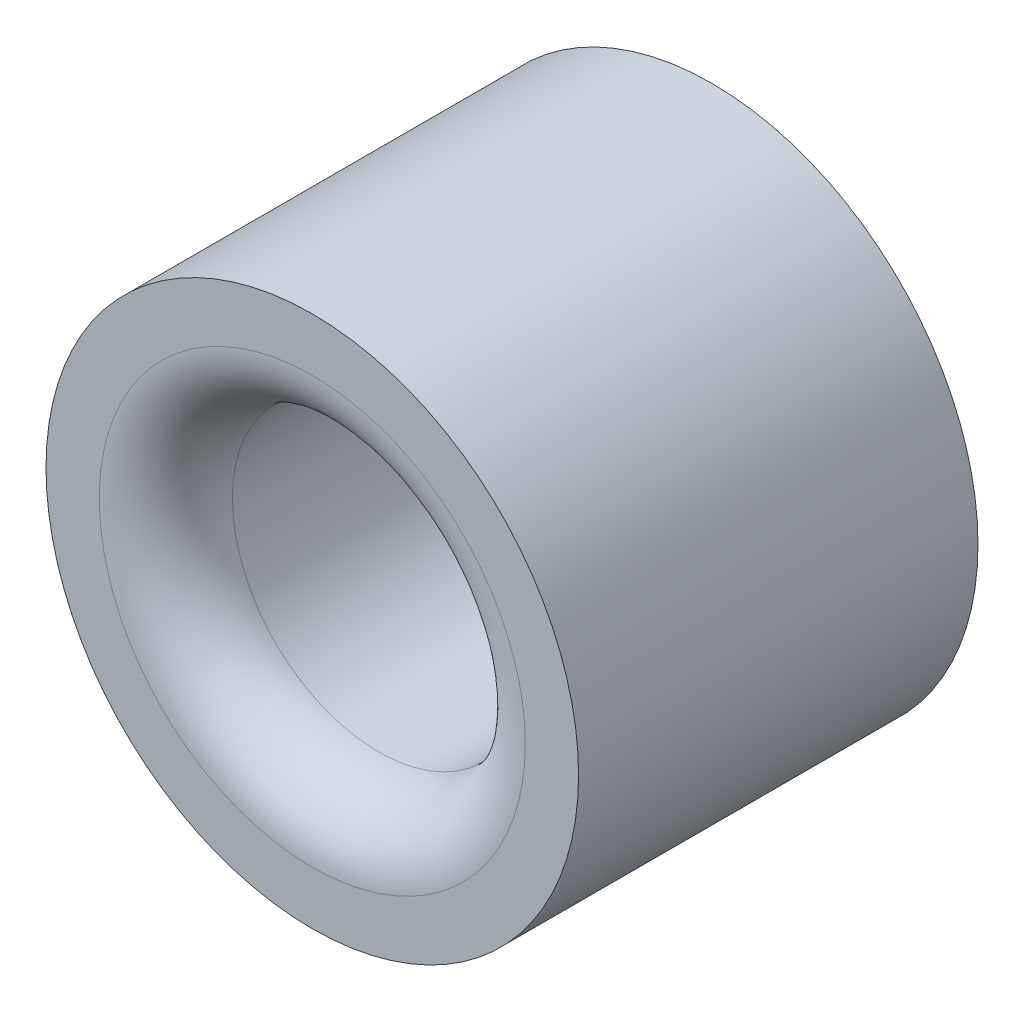
SolidWorks part; units mm, degrees
material "6061 合金"
ref_plane "前视基准面" through (0, 0, 0) normal (0, 0, 1) x (1, 0, 0)
ref_plane "上视基准面" through (0, 0, 0) normal (0, 1, 0) x (1, 0, 0)
ref_plane "右视基准面" through (0, 0, 0) normal (1, 0, 0) x (0, 0, -1)
sketch "草图1" plane through (0, 0, 0) normal (0, 0, 1) x (1, 0, 0)
  circle A0 centre (0, 0) radius 2
  circle A1 centre (0, 0) radius 1.1
  dimension "D1" = 4
  dimension "D2" = 2.2
extrude "凸台-拉伸1" add sketch "草图1" along normal blind 3
fillet "圆角1" radius 0.5 2 edges at (1.1, 0, 0) (1.1, 0, 3)
